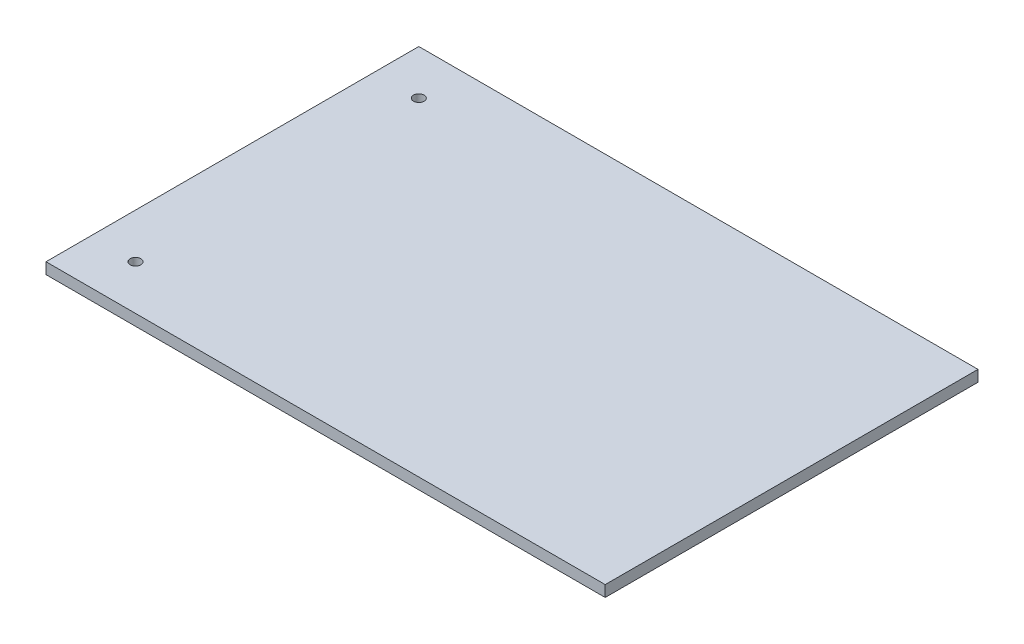
SolidWorks part; units mm, degrees
ref_plane "Front Plane" through (0, 0, 0) normal (0, 0, 1) x (1, 0, 0)
ref_plane "Top Plane" through (0, 0, 0) normal (0, 1, 0) x (1, 0, 0)
ref_plane "Right Plane" through (0, 0, 0) normal (1, 0, 0) x (0, 0, -1)
sketch "Sketch1" plane through (0, 0, 0) normal (0, 1, 0) x (1, 0, 0)
  line L1 (75, -50) -> (-75, -50)
  line L2 (75, -50) -> (75, 50)
  line L3 (75, 50) -> (-75, 50)
  line L4 (-75, -50) -> (-75, 50)
  line L5 (75, -50) -> (-75, 50) construction
  line L6 (75, 50) -> (-75, -50) construction
  point P0 (0, 0)
  dimension "D1" = 150
  dimension "D2" = 100
extrude "Boss-Extrude1" add sketch "Sketch1" along normal blind 3
sketch "Sketch2" plane through (0, 3, 0) normal (0, 1, 0) x (1, 0, 0)
  line L0 (0, 0) -> (-122.3191, 0) construction
  line L1 (-122.3191, 0) -> (115.1579, 0) construction
  line L2 (0, 73.5477) -> (0, -98.9538) construction
  line L3 (75, 50) -> (-75, 50) construction
  line L4 (-75, 50) -> (-75, -50) construction
  circle A0 centre (-63, 38) radius 1.425
  dimension "D1" = 2.85
  dimension "D2" = 12
  dimension "D3" = 12
extrude "Cut-Extrude1" cut sketch "Sketch2" against normal blind 10
pattern_linear "LPattern1" count 1 spacing 126 along (-1, 0, 0) count 2 spacing 76 along (0, 0, 1) of "Cut-Extrude1"
sketch "Sketch3" [suppressed] plane through (0, 3, 0) normal (0, 1, 0) x (1, 0, 0)
  line L0 (47, 37) -> (-47, 37) construction
  line L1 (-47, 37) -> (-47, -37) construction
  circle A0 centre (-38, 28) radius 1.425
  dimension "D1" = 2.85
  dimension "D2" = 9
  dimension "D3" = 9
extrude "Cut-Extrude2" [suppressed] cut sketch "Sketch3" against normal blind 10
pattern_linear "LPattern2" [suppressed] count 2 spacing 76 count 2 spacing 56
sketch "Sketch4" [suppressed] plane through (0, 3, 0) normal (0, 1, 0) x (1, 0, 0)
  line L0 (75, 37) -> (-75, 37) construction
  line L1 (-75, 37) -> (-75, -37) construction
  circle A0 centre (-63, 28) radius 1.425
  dimension "D1" = 2.85
  dimension "D2" = 9
  dimension "D3" = 12
extrude "Cut-Extrude3" [suppressed] cut sketch "Sketch4" against normal blind 10
pattern_linear "LPattern3" [suppressed] count 2 spacing 126 count 2 spacing 56
sketch "Sketch5" [suppressed] plane through (0, 3, 0) normal (0, 1, 0) x (1, 0, 0)
  line L0 (-75, 50) -> (-75, -50) construction
  line L1 (-75, -50) -> (75, -50) construction
  line L3 (-1.7, -25) -> (-81.1724, -25) construction
  line L4 (-6.8, 27.4) -> (-34.7, 27.4) construction
  circle A0 centre (-34.7, 27.4) radius 1.6
  circle A1 centre (-6.8, 27.4) radius 1.6
  circle A2 centre (-1.7, -25) radius 1.6
  circle A4 centre (-50, -23.4) radius 1.6
  dimension "D1" = 3.2
  dimension "D2" = 27.9
  dimension "D3" = 5.1
  dimension "D4" = 50.8
  dimension "D5" = 48.3
  dimension "D6" = 25
  dimension "D7" = 25
extrude "Cut-Extrude4" [suppressed] cut sketch "Sketch5" against normal blind 10
sketch "Sketch6" [suppressed] plane through (0, 0, 0) normal (0, -1, 0) x (1, 0, 0)
  line L0 (-63, 38) -> (100.028, 38) construction
  line L1 (75, 50) -> (75, -50) construction
  line L2 (63, 38) -> (63, -100.5192) construction
  line L3 (-63, -38) -> (102.189, -38) construction
  circle A0 centre (63, 38) radius 1.425
  circle A3 centre (63, -38) radius 1.425
  dimension "D2" = 2.85
  dimension "D1" = 12
extrude "Cut-Extrude5" [suppressed] cut sketch "Sketch6" against normal blind 10
